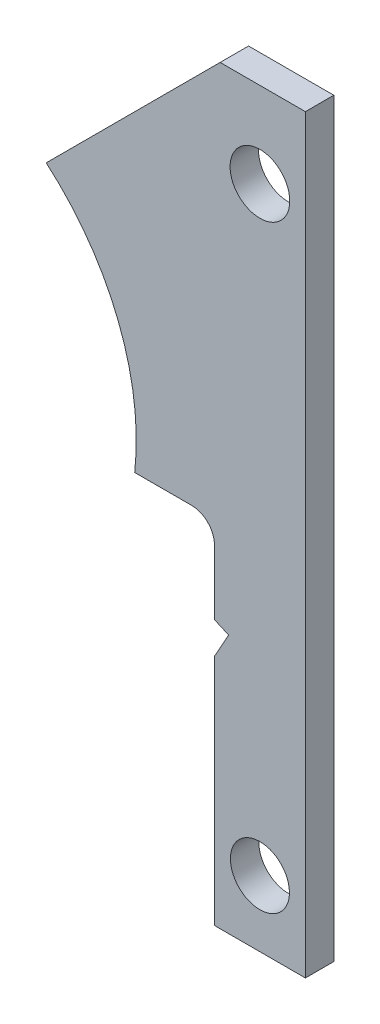
SolidWorks part; units mm, degrees
ref_plane "Front Plane" through (0, 0, 0) normal (0, 0, 1) x (1, 0, 0)
ref_plane "Top Plane" through (0, 0, 0) normal (0, 1, 0) x (1, 0, 0)
ref_plane "Right Plane" through (0, 0, 0) normal (1, 0, 0) x (0, 0, -1)
sketch "Model" plane through (0, 0, 0) normal (0, 0, 1) x (1, 0, 0)
  line L0 (869.6, 129.8) -> (854.6, 129.8)
  line L1 (854.6, 129.8) -> (854.6, 124.8)
  line L2 (820.0281, 59.8) -> (849.6, 59.8)
  line L3 (853.6, 55.8) -> (853.6, 44.4002)
  line L4 (853.6, 44.4002) -> (856.1, 43.3)
  line L5 (856.1, 43.3) -> (853.6, 38.8294)
  line L6 (853.6, 38.8294) -> (853.6, -2.2)
  line L7 (853.6, -2.2) -> (869.6, -2.2)
  line L8 (869.6, -2.2) -> (869.6, 129.8)
  arc A0 (815.1233, 79.1972) -> (854.6, 124.8) centre (806.7231, 126.3571) ccw
  arc A1 (820.0281, 59.8) -> (815.1233, 79.1972) centre (795.0764, 63.8094) ccw
  arc A2 (853.6, 55.8) -> (849.6, 59.8) centre (849.6, 55.8) ccw
  circle A3 centre (861.6, 9.3915) radius 5.1919
  circle A4 centre (861.6, 114.8) radius 5.25
extrude "Boss-Extrude1" add sketch "Model" along normal blind 5
sketch "Sketch4" plane through (0, 0, 0) normal (0, 0, 1) x (1, 0, 0)
  line L0 (854.6, 129.8) -> (799.7005, 74.9005)
  line L1 (799.7005, 74.9005) -> (857.0819, 78.4517)
  line L2 (857.0819, 78.4517) -> (855.6766, 119.4362)
  line L3 (855.6766, 119.4362) -> (858.6479, 128.485)
  line L4 (858.6479, 128.485) -> (854.6, 129.8)
extrude "Boss-Extrude2" add sketch "Sketch4" along normal blind 5
sketch "Sketch3" plane through (0, 0, 0) normal (0, 0, -1) x (-1, 0, 0)
  circle A1 centre (-861.6, 114.8) radius 5.25 construction
  circle A2 centre (-794.6, 64.8) radius 45.25
  dimension "D1" = 67
  dimension "D2" = 50
extrude "Cut-Extrude1" cut sketch "Sketch3" against normal blind 6
